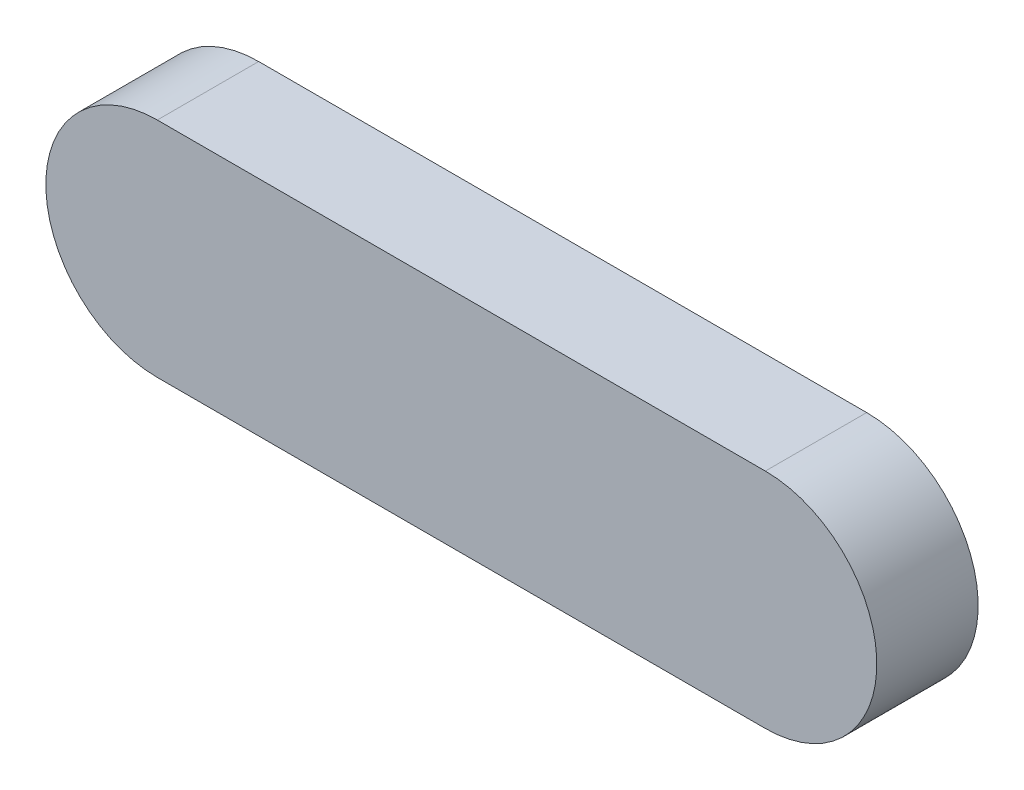
SolidWorks part; units mm, degrees
ref_plane "Front Plane" through (0, 0, 0) normal (0, 0, 1) x (1, 0, 0)
ref_plane "Top Plane" through (0, 0, 0) normal (0, 1, 0) x (1, 0, 0)
ref_plane "Right Plane" through (0, 0, 0) normal (1, 0, 0) x (0, 0, -1)
sketch "草图3" plane through (0, 0, 0) normal (0, 0, 1) x (1, 0, 0)
  line L0 (20, 50) -> (80, 50) construction
  line L1 (20, 61) -> (80, 61)
  line L2 (20, 39) -> (80, 39)
  arc A0 (20, 61) -> (20, 39) centre (20, 50) ccw
  arc A1 (80, 39) -> (80, 61) centre (80, 50) ccw
  point P2 (50, 50)
  point P7 (0, 0)
  dimension "width" = 22
  dimension "end1_x" = 20
  dimension "end2_x" = 80
  dimension "end1_y" = 50
extrude "RockerLink" add sketch "草图3" along normal blind 10
